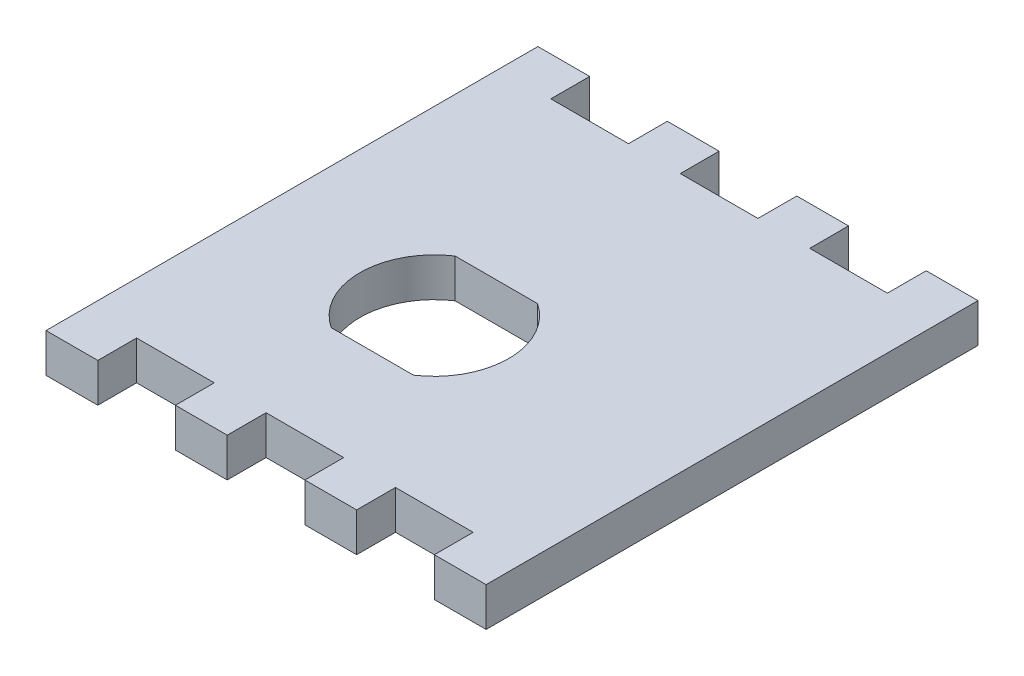
SolidWorks part; units mm, degrees
ref_plane "Front Plane" through (0, 0, 0) normal (0, 0, 1) x (1, 0, 0)
ref_plane "Top Plane" through (0, 0, 0) normal (0, 1, 0) x (1, 0, 0)
ref_plane "Right Plane" through (0, 0, 0) normal (1, 0, 0) x (0, 0, -1)
sketch "Sketch1" plane through (0, 0, 0) normal (0, 1, 0) x (1, 0, 0)
  line L1 (-17, -19) -> (17, -19)
  line L2 (-17, -19) -> (-17, 19)
  line L3 (-17, 19) -> (17, 19)
  line L4 (17, -19) -> (17, 19)
  line L5 (-17, -19) -> (17, 19) construction
  line L6 (-17, 19) -> (17, -19) construction
  point P0 (0, 0)
  dimension "D1" = 34
  dimension "D2" = 38
extrude "Boss-Extrude1" add sketch "Sketch1" along normal blind 3
sketch "Sketch3" plane through (0, 3, 0) normal (0, 1, 0) x (1, 0, 0)
  line L0 (17, 19) -> (-17, 19) construction
  line L1 (-13, 19) -> (-7, 19)
  line L2 (-13, 19) -> (-13, 16)
  line L3 (-13, 16) -> (-7, 16)
  line L4 (-7, 19) -> (-7, 16)
  line L5 (-17, 19) -> (-17, -19) construction
  dimension "D1" = 6
  dimension "D2" = 3
  dimension "D3" = 4
extrude "Cut-Extrude2" cut sketch "Sketch3" against normal blind 3
pattern_linear "LPattern2" count 3 spacing 10 along (1, 0, 0) count 2 spacing 35 along (0, 0, 1) of "Cut-Extrude2"
sketch "Sketch4" plane through (0, 3, 0) normal (0, 1, 0) x (1, 0, 0)
  line L1 (-6.1784, -7.7917) -> (0.1784, -7.7917)
  line L2 (-17, 19) -> (-17, -19) construction
  line L3 (-6.1833, 1.7884) -> (0.1833, 1.7884)
  arc A0 (-6.1833, 1.7884) -> (-6.1784, -7.7917) centre (-3, -3) ccw
  arc A1 (0.1784, -7.7917) -> (0.1833, 1.7884) centre (-3, -3) ccw
  dimension "D1" = 11.5
  dimension "D3" = 22
  dimension "D4" = 14
extrude "Cut-Extrude4" cut sketch "Sketch4" against normal blind 3
